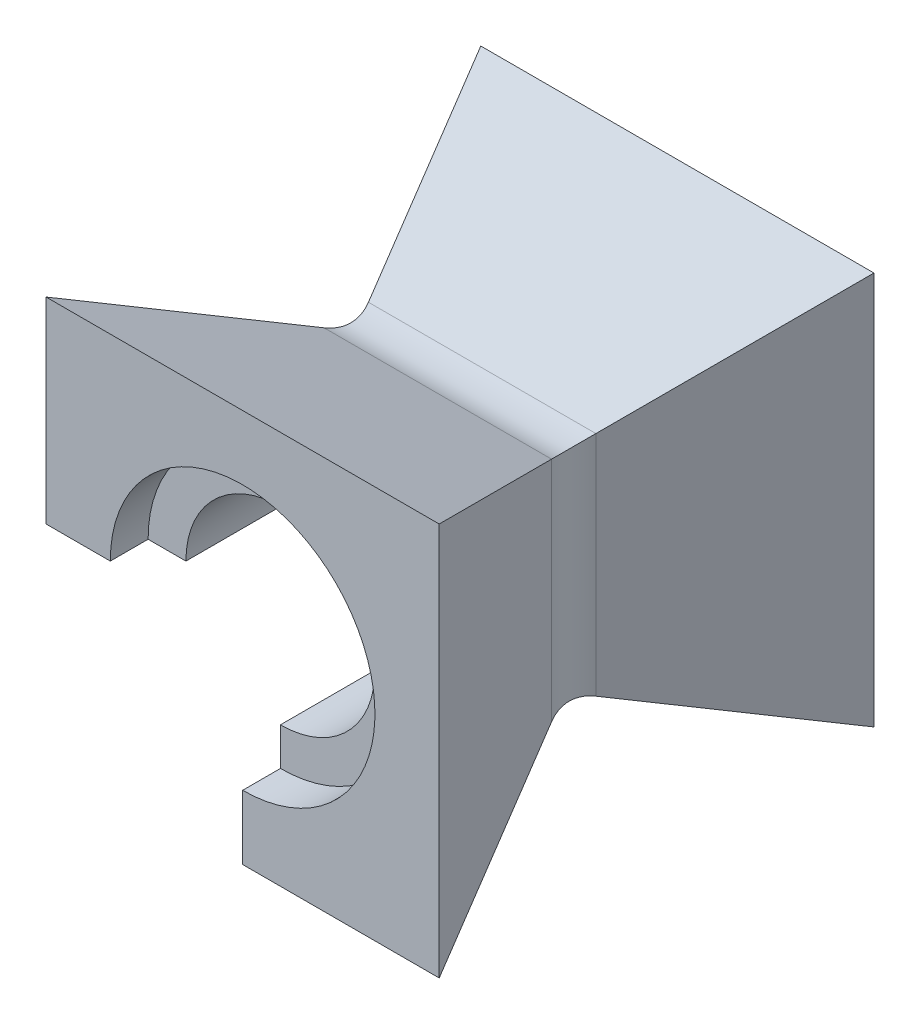
SolidWorks part; units mm, degrees
material "Cast Stainless Steel"
ref_plane "Front Plane" through (0, 0, 0) normal (0, 0, 1) x (1, 0, 0)
ref_plane "Top Plane" through (0, 0, 0) normal (0, 1, 0) x (1, 0, 0)
ref_plane "Right Plane" through (0, 0, 0) normal (1, 0, 0) x (0, 0, -1)
sketch "Sketch4" plane through (0, 0, 0) normal (0, 0, 1) x (1, 0, 0)
  line L0 (104, 104) -> (0, 0) construction
  line L1 (0, 0) -> (104, 0)
  line L2 (0, 0) -> (0, 104)
  line L3 (0, 104) -> (104, 104)
  line L4 (104, 0) -> (104, 104)
  line L5 (0, 104) -> (104, 0) construction
  dimension "D1" = 104
  dimension "D2" = 104
extrude "Boss-Extrude2" add sketch "Sketch4" along normal blind 57.5 draft 23
mirror "Mirror2" about plane through (0, 0, 57.5) normal (0, 0, -1) of "Boss-Extrude2"
sketch "Sketch6" plane through (0, 0, 115) normal (0, 0, 1) x (1, 0, 0)
  line L0 (104, 0) -> (104, 104) construction
  line L1 (104, 104) -> (0, 104) construction
  circle A0 centre (52, 52) radius 25
  dimension "D1" = 50
  dimension "D2" = 52
  dimension "D3" = 52
extrude "Cut-Extrude1" cut sketch "Sketch6" against normal blind 179.5
sketch "Sketch8" plane through (0, 0, 0) normal (0, 0, 1) x (1, 0, 0)
  line L0 (52, 0) -> (52, 104) construction
  line L1 (0, 52) -> (104, 52) construction
  line L2 (0, 104) -> (0, 0) construction
  arc A0 (52, 17) -> (17, 52) centre (52, 52) ccw
  arc A1 (52, 27) -> (27, 52) centre (52, 52) ccw
  point P6 (52, 52)
  point P9 (52, 52)
  dimension "D1" = 70
  dimension "D2" = 50
extrude "Cut-Extrude-Thin1" cut sketch "Sketch8" along normal blind 10 thin
sketch "Sketch9" plane through (0, 0, 0) normal (0, 0, -1) x (-1, 0, 0)
  line L0 (-27, 52) -> (0, 52)
  line L1 (0, 104) -> (0, 0) construction
  line L2 (0, 52) -> (0, 0)
  line L3 (0, 0) -> (-52, 0)
  line L4 (0, 0) -> (-104, 0) construction
  line L5 (-52, 0) -> (-52, 27)
  line L6 (-52, 27) -> (-52, 52)
  line L7 (-52, 52) -> (-27, 52)
extrude "Cut-Extrude3" cut sketch "Sketch9" against normal blind 124
sketch "Sketch10" plane through (0, 0, 115) normal (0, 0, 1) x (1, 0, 0)
  circle A0 centre (52, 52) radius 35
  dimension "D1" = 70
extrude "Cut-Extrude4" cut sketch "Sketch10" against normal blind 10
fillet "Fillet9" radius 15 1 edges at (65.7963, 24.4073, 57.5)
fillet "Fillet10" radius 15 3 edges at (24.4073, 65.7963, 57.5) (52, 79.5927, 57.5) (79.5927, 51.3523, 57.5)
